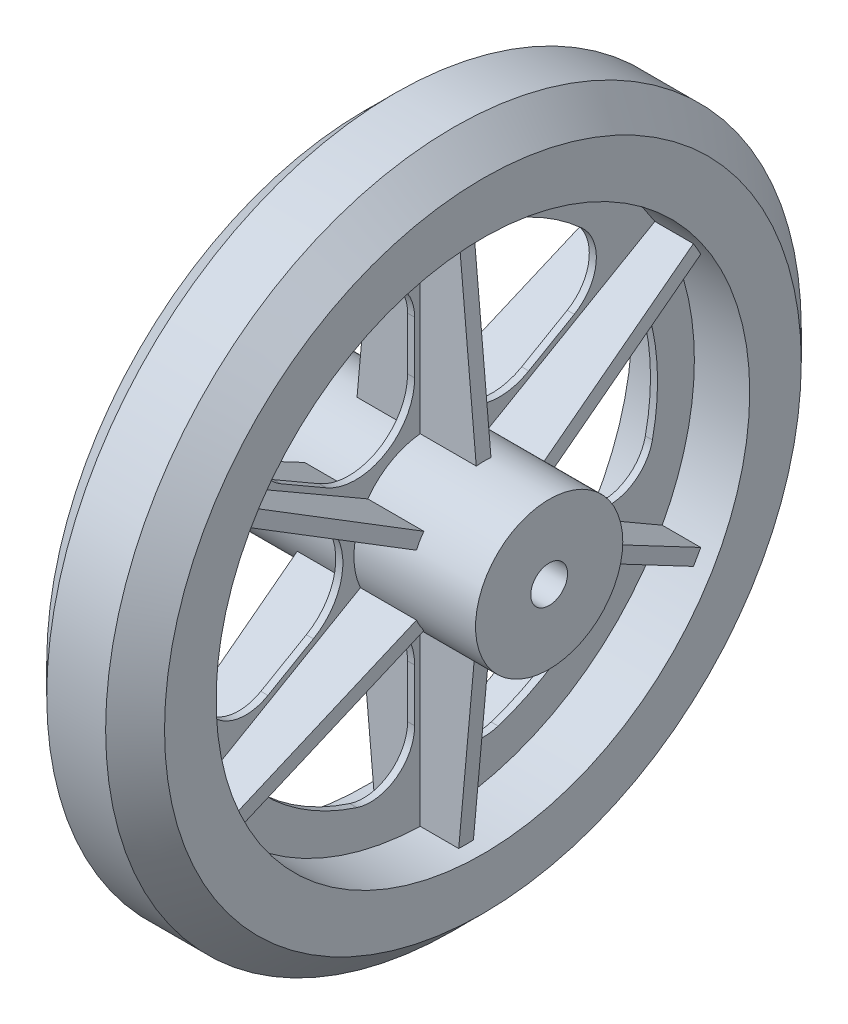
SolidWorks part; units mm, degrees
ref_plane "Front Plane" through (0, 0, 0) normal (0, 0, 1) x (1, 0, 0)
ref_plane "Top Plane" through (0, 0, 0) normal (0, 1, 0) x (1, 0, 0)
ref_plane "Right Plane" through (0, 0, 0) normal (1, 0, 0) x (0, 0, -1)
sketch "Sketch1" plane through (0, 0, 0) normal (1, 0, 0) x (0, 0, -1)
  circle A0 centre (0, 0) radius 15.875
  dimension "D2" = 31.75
extrude "Boss-Extrude1" add sketch "Sketch1" along normal blind 26.9875 and the other way blind 26.9875
sketch "Sketch2" plane through (0, 0, 0) normal (1, 0, 0) x (0, 0, -1)
  circle A0 centre (0, 0) radius 75
  dimension "D1" = 150
extrude "Boss-Extrude2" add sketch "Sketch2" along normal blind 0.762 and the other way blind 0.762
sketch "Sketch3" plane through (0, 0, 0) normal (1, 0, 0) x (0, 0, -1)
  circle A0 centre (0, 0) radius 75 construction
  circle A1 centre (0, 0) radius 75
  circle A2 centre (0, 0) radius 57.5375
  dimension "D1" = 17.4625
extrude "Boss-Extrude3" add sketch "Sketch3" along normal blind 12.7 and the other way blind 12.7
sketch "Sketch4" plane through (0, 0, 0) normal (1, 0, 0) x (0, 0, -1)
  line L0 (0, 75) -> (0, -75) construction
  line L2 (-64.9519, -37.5) -> (64.9519, 37.5) construction
  line L4 (31.6409, 21.4758) -> (21.8281, 15.8104)
  line L5 (2.7781, 38.1397) -> (2.7781, 26.8089)
  circle A0 centre (0, 0) radius 75 construction
  circle A1 centre (0, 0) radius 75 construction
  arc A2 (15.2273, 47.2048) -> (33.2669, 36.7896) centre (0, 0) cw
  arc A3 (21.8281, 15.8104) -> (2.7781, 26.8089) centre (15.4781, 26.8089) cw
  arc A4 (33.2669, 36.7896) -> (31.6409, 21.4758) centre (26.8784, 29.7247) cw
  arc A5 (15.2273, 47.2048) -> (2.7781, 38.1397) centre (12.3031, 38.1397) ccw
  dimension "D4" = 25.4
  dimension "D5" = 12.7
  dimension "D6" = 9.525
  dimension "D1" = 60
  dimension "D2" = 5.5562
  dimension "D3" = 5.5562
extrude "Cut-Extrude1" cut sketch "Sketch4" against normal through all and the other way through all
sketch "Sketch5" plane through (0, 0, 0) normal (0, 1, 0) x (1, 0, 0)
  line L1 (-14.2875, -1.5875) -> (14.2875, -1.5875)
  line L2 (-14.2875, -1.5875) -> (-14.2875, 1.5875)
  line L3 (-14.2875, 1.5875) -> (14.2875, 1.5875)
  line L4 (14.2875, -1.5875) -> (14.2875, 1.5875)
  line L5 (-14.2875, -1.5875) -> (14.2875, 1.5875) construction
  line L6 (-14.2875, 1.5875) -> (14.2875, -1.5875) construction
  line L7 (26.9875, -15.875) -> (26.9875, 15.875) construction
  point P0 (0, 0)
  dimension "D1" = 12.7
  dimension "D2" = 3.175
ref_plane "Plane1" through (0, 70, 0) normal (0, 1, 0) x (-1, 0, 0)
sketch "Sketch6" plane through (0, 70, 0) normal (0, 1, 0) x (-1, 0, 0)
  line L1 (7.9375, 1.5875) -> (-7.9375, 1.5875)
  line L2 (7.9375, 1.5875) -> (7.9375, -1.5875)
  line L3 (7.9375, -1.5875) -> (-7.9375, -1.5875)
  line L4 (-7.9375, 1.5875) -> (-7.9375, -1.5875)
  line L5 (7.9375, 1.5875) -> (-7.9375, -1.5875) construction
  line L6 (7.9375, -1.5875) -> (-7.9375, 1.5875) construction
  point P0 (0, 0)
  dimension "D1" = 15.875
  dimension "D2" = 3.175
loft "Loft1" add profiles "Sketch5", "Sketch6"
pattern_circular "CirPattern1" count 6 over 360 about axis through (0, 0, 0) along (1, 0, 0) of "Cut-Extrude1", "Loft1"
sketch "Sketch9" plane through (0, 0, 0) normal (1, 0, 0) x (0, 0, -1)
  circle A0 centre (0, 0) radius 3.9688
  dimension "D1" = 7.9375
extrude "Cut-Extrude2" cut sketch "Sketch9" against normal through all and the other way through all
chamfer "Chamfer1" distance 6.35 angle 45 2 edges at (-12.7, 0, -75) (12.7, 0, -75)
